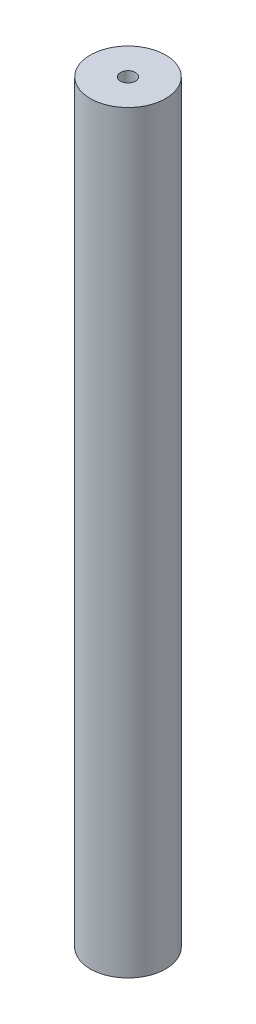
SolidWorks part; units mm, degrees
ref_plane "Front Plane" through (0, 0, 0) normal (0, 0, 1) x (1, 0, 0)
ref_plane "Top Plane" through (0, 0, 0) normal (0, 1, 0) x (1, 0, 0)
ref_plane "Right Plane" through (0, 0, 0) normal (1, 0, 0) x (0, 0, -1)
sketch "Sketch1" plane through (0, 0, 0) normal (0, 1, 0) x (1, 0, 0)
  line L0 (0, 0) -> (0, 65.5458) construction
  line L1 (0, 0) -> (-59.0385, 0) construction
  circle A0 centre (0, 0) radius 50
  circle A1 centre (0, 0) radius 10
  dimension "D1" = 100
  dimension "D2" = 20
extrude "Boss-Extrude1" add sketch "Sketch1" along normal blind 1000
